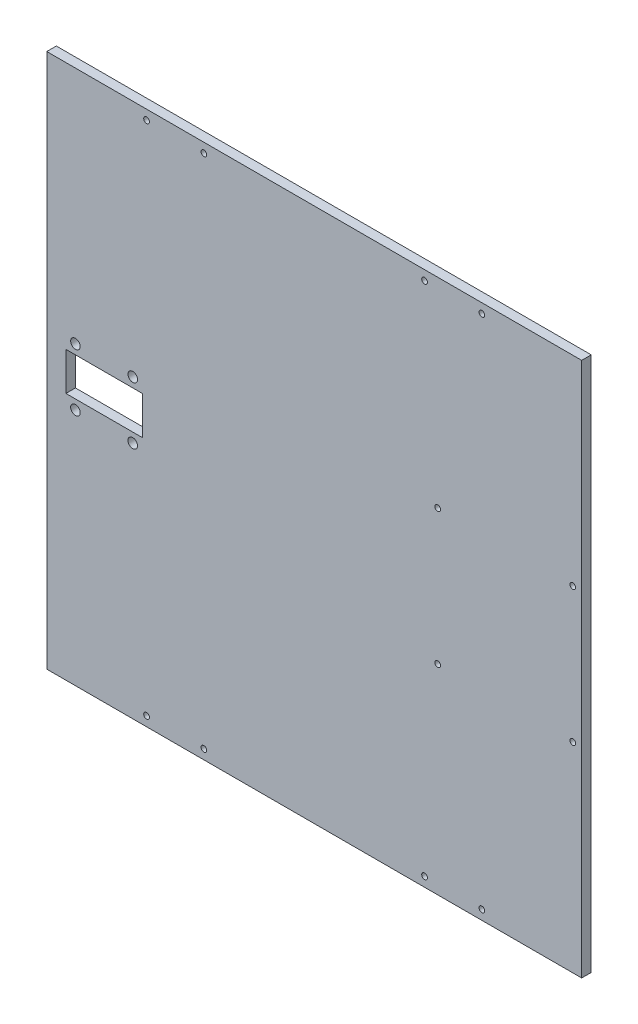
SolidWorks part; units mm, degrees
ref_plane "前视基准面" through (0, 0, 0) normal (0, 0, 1) x (1, 0, 0)
ref_plane "上视基准面" through (0, 0, 0) normal (0, 1, 0) x (1, 0, 0)
ref_plane "右视基准面" through (0, 0, 0) normal (1, 0, 0) x (0, 0, -1)
sketch "草图1" plane through (0, 0, 0) normal (0, 0, 1) x (1, 0, 0)
  line L0 (0, 66.0055) -> (0, 0) construction
  line L1 (-140, -140) -> (140, -140)
  line L2 (-140, -140) -> (-140, 140)
  line L3 (-140, 140) -> (140, 140)
  line L4 (140, -140) -> (140, 140)
  line L5 (-140, -140) -> (140, 140) construction
  line L6 (-140, 140) -> (140, -140) construction
  line L7 (0, 0) -> (89.6595, 0) construction
  line L9 (135.3553, -35.3553) -> (64.6447, -35.3553) construction
  line L10 (135.3553, -35.3553) -> (135.3553, 35.3553) construction
  line L11 (135.3553, 35.3553) -> (64.6447, 35.3553) construction
  line L12 (64.6447, -35.3553) -> (64.6447, 35.3553) construction
  line L13 (135.3553, -35.3553) -> (64.6447, 35.3553) construction
  line L14 (135.3553, 35.3553) -> (64.6447, -35.3553) construction
  line L15 (-90, 10) -> (-130, 10)
  line L16 (-90, 10) -> (-90, -10)
  line L17 (-90, -10) -> (-130, -10)
  line L18 (-130, 10) -> (-130, -10)
  circle A0 centre (-87.76, 135) radius 1.5
  circle A1 centre (-57.76, 135) radius 1.5
  circle A2 centre (57.76, 135) radius 1.5
  circle A3 centre (87.76, 135) radius 1.5
  circle A4 centre (87.76, -135) radius 1.5
  circle A5 centre (57.76, -135) radius 1.5
  circle A6 centre (-57.76, -135) radius 1.5
  circle A7 centre (-87.76, -135) radius 1.5
  circle A8 centre (64.6447, 35.3553) radius 1.5
  circle A9 centre (135.3553, 35.3553) radius 1.5
  circle A10 centre (64.6447, -35.3553) radius 1.5
  circle A11 centre (135.3553, -35.3553) radius 1.5
  circle A18 centre (-95, 15) radius 2.5
  circle A19 centre (-125, 15) radius 2.5
  circle A20 centre (-125, -15) radius 2.5
  circle A21 centre (-95, -15) radius 2.5
  point P0 (0, 0)
  point P25 (100, 0)
  point P34 (-100, 0)
  dimension "D3" = 3
  dimension "D4" = 3
  dimension "D10" = 3
  dimension "D11" = 3
  dimension "D12" = 3
  dimension "D13" = 3
  dimension "D14" = 10
  dimension "D16" = 40
  dimension "D21" = 5
  dimension "D22" = 5
  dimension "D23" = 5
  dimension "D24" = 5
  dimension "D25" = 5
  dimension "D18" = 5
  dimension "D19" = 5
  dimension "D1" = 280
  dimension "D2" = 280
  dimension "D5" = 30
  dimension "D6" = 52.24
  dimension "D7" = 5
  dimension "D8" = 100
  dimension "D9" = 40
  dimension "D15" = 40
  dimension "D17" = 20
  dimension "D20" = 10
  dimension "D26" = 5
  dimension "D27" = 5
  dimension "D28" = 5
  dimension "D29" = 5
  dimension "D30" = 5
extrude "凸台-拉伸1" add sketch "草图1" along normal blind 5
